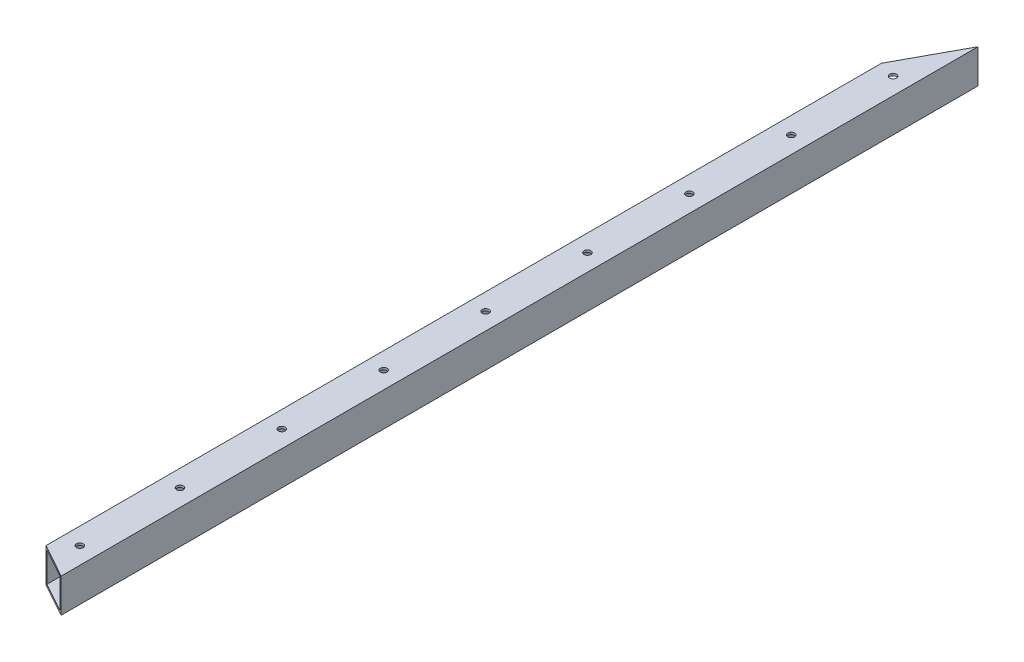
SolidWorks part; units mm, degrees
ref_plane "Front Plane" through (0, 0, 0) normal (0, 0, 1) x (1, 0, 0)
ref_plane "Top Plane" through (0, 0, 0) normal (0, 1, 0) x (1, 0, 0)
ref_plane "Right Plane" through (0, 0, 0) normal (1, 0, 0) x (0, 0, -1)
sketch "Sketch1" plane through (0, 0, 0) normal (0, 0, 1) x (1, 0, 0)
  line L1 (0, 0) -> (25.4, 0)
  line L2 (0, 0) -> (0, 25.4)
  line L3 (0, 25.4) -> (25.4, 25.4)
  line L4 (25.4, 0) -> (25.4, 25.4)
  line L5 (1.5875, 1.5875) -> (23.8125, 1.5875)
  line L6 (1.5875, 1.5875) -> (1.5875, 23.8125)
  line L7 (1.5875, 23.8125) -> (23.8125, 23.8125)
  line L8 (23.8125, 1.5875) -> (23.8125, 23.8125)
  dimension "D1" = 25.4
  dimension "D2" = 1.5875
  dimension "D3" = 1.5875
  dimension "D4" = 1.5875
  dimension "D5" = 1.5875
extrude "Boss-Extrude1" add sketch "Sketch1" along normal blind 685.8
sketch "Sketch3" plane through (0, 25.4, 0) normal (0, 1, 0) x (1, 0, 0)
  line L0 (0, -342.9) -> (25.4, -342.9) construction
  line L1 (25.4, -685.8) -> (25.4, 0) construction
  line L4 (0, -685.8) -> (0, 0) construction
  line L5 (25.4, 0) -> (0, 0) construction
  line L8 (0, 0) -> (0, -46.781)
  line L9 (0, -46.781) -> (25.4, 0)
  line L10 (25.4, 0) -> (0, 0)
  line L11 (0, -685.8) -> (0, -671.7206)
  line L12 (0, -671.7206) -> (25.4, -685.8)
  line L13 (25.4, -685.8) -> (0, -685.8)
  circle A14 centre (12.7, -50.8) radius 2.54
  circle A17 centre (12.7, -127) radius 2.54
  circle A18 centre (12.7, -203.2) radius 2.54
  circle A19 centre (12.7, -279.4) radius 2.54
  circle A20 centre (12.7, -355.6) radius 2.54
  circle A21 centre (12.7, -431.8) radius 2.54
  circle A22 centre (12.7, -508) radius 2.54
  circle A23 centre (12.7, -584.2) radius 2.54
  circle A25 centre (12.7, -660.4) radius 2.54 [skipped]
  circle A26 centre (12.7, -659.13) radius 2.54
  point P4 (0, 0)
  dimension "D6" = 12.7
  dimension "D2" = 26.67
  dimension "D5" = 5.08
  dimension "D7" = 50.8
  dimension "D8" = 9
  dimension "D10" = 28.5
  dimension "D11" = 61
extrude "Cut-Extrude2" cut sketch "Sketch3" against normal through all
